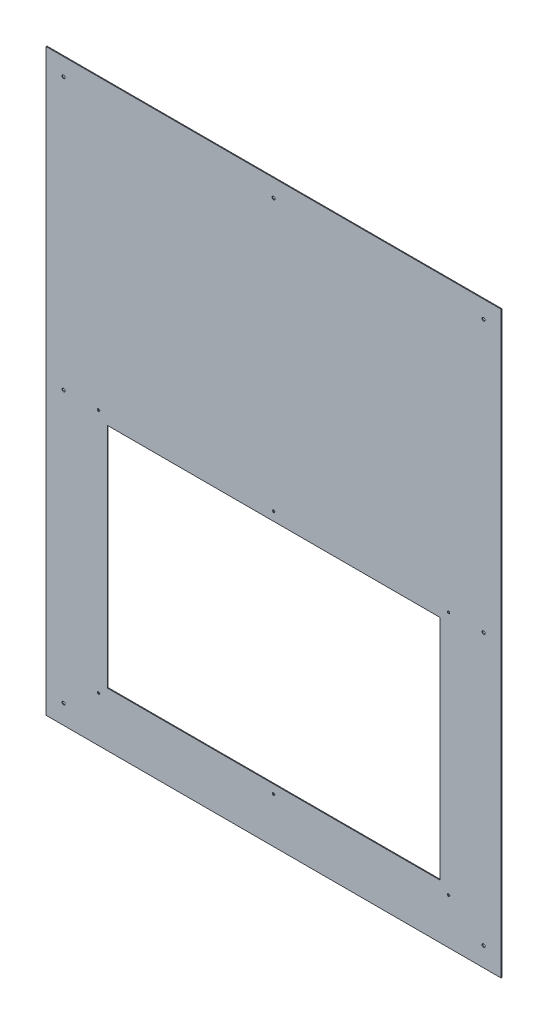
SolidWorks part; units mm, degrees
material "1023 Carbon Steel Sheet (SS)"
ref_plane "Front Plane" through (0, 0, 0) normal (0, 0, 1) x (1, 0, 0)
ref_plane "Top Plane" through (0, 0, 0) normal (0, 1, 0) x (1, 0, 0)
ref_plane "Right Plane" through (0, 0, 0) normal (1, 0, 0) x (0, 0, -1)
sketch "Sketch1" plane through (0, 0, 0) normal (0, 0, 1) x (1, 0, 0)
  line L1 (0, 0) -> (660.4, 0)
  line L2 (0, 0) -> (0, 840.74)
  line L3 (0, 840.74) -> (660.4, 840.74)
  line L4 (660.4, 0) -> (660.4, 840.74)
  dimension "D1" = 840.74
  dimension "D2" = 660.4
extrude "Boss-Extrude1" add sketch "Sketch1" along normal blind 1.2192
sketch "Sketch2" plane through (0, 0, 1.2192) normal (0, 0, 1) x (1, 0, 0)
  line L0 (660.4, 0) -> (660.4, 840.74) construction
  line L1 (25.4, 815.34) -> (635, 815.34) construction
  line L2 (25.4, 815.34) -> (25.4, 27.94) construction
  line L3 (25.4, 27.94) -> (635, 27.94) construction
  line L4 (635, 815.34) -> (635, 27.94) construction
  line L5 (660.4, 840.74) -> (0, 840.74) construction
  line L6 (0, 840.74) -> (0, 0) construction
  point P12 (25.4, 421.64)
  point P13 (25.4, 815.34)
  point P14 (25.4, 27.94)
  point P15 (330.2, 815.34)
  point P16 (635, 421.64)
  point P17 (635, 815.34)
  point P19 (635, 27.94)
  dimension "D1" = 25.4
  dimension "D2" = 25.4
  dimension "D3" = 25.4
  dimension "D4" = 393.7
hole_wizard "#8 Clearance Hole1" positions "Sketch4" profile "Sketch3" hole size "#8" standard "ANSI Inch" end condition through all
sketch "Sketch4" plane through (0, 0, 1.2192) normal (0, 0, 1) x (1, 0, 0)
  point P0 (25.4, 815.34)
  point P2 (330.2, 815.34)
  point P4 (635, 815.34)
  point P11 (25.4, 421.64)
  point P14 (25.4, 27.94)
  point P17 (635, 27.94)
  point P20 (635, 421.64)
sketch "Sketch3" plane through (25.4, 815.34, 1.2192) normal (1, 0, 0) x (0, -1, 0)
  line L0 (0, 0) -> (0, 1.2192)
  line L1 (0, 1.2192) -> (2.2479, 1.2192)
  line L2 (2.2479, 1.2192) -> (2.2479, 0)
  line L5 (2.2479, 0) -> (0, 0)
  line L11 (0, -6.35) -> (0, 107.95) construction
  dimension "Thru Hole Dia." = 4.4958
  dimension "Thru Hole Depth" = 1.2192
sketch "Sketch5" plane through (0, 0, 1.2192) normal (0, 0, 1) x (1, 0, 0)
  line L0 (0, 840.74) -> (0, 0) construction
  line L1 (88.9, 408.94) -> (571.5, 408.94)
  line L2 (88.9, 408.94) -> (88.9, 78.74)
  line L3 (88.9, 78.74) -> (571.5, 78.74)
  line L4 (571.5, 408.94) -> (571.5, 78.74)
  line L7 (660.4, 840.74) -> (0, 840.74) construction
  dimension "D1" = 482.6
  dimension "D2" = 330.2
  dimension "D3" = 88.9
  dimension "D4" = 431.8
extrude "Cut-Extrude1" cut sketch "Sketch5" against normal blind 2.54
sketch "Sketch6" plane through (0, 0, 1.2192) normal (0, 0, 1) x (1, 0, 0)
  line L0 (571.5, 408.94) -> (88.9, 408.94) construction
  line L1 (76.2, 421.64) -> (584.2, 421.64)
  line L2 (76.2, 421.64) -> (76.2, 66.04)
  line L3 (76.2, 66.04) -> (584.2, 66.04)
  line L4 (584.2, 421.64) -> (584.2, 66.04)
  line L5 (88.9, 78.74) -> (571.5, 78.74) construction
  line L6 (571.5, 78.74) -> (571.5, 408.94) construction
  line L7 (88.9, 408.94) -> (88.9, 78.74) construction
  point P12 (330.2, 421.64)
  point P13 (76.2, 421.64)
  point P14 (330.2, 66.04)
  point P15 (584.2, 421.64)
  point P16 (584.2, 66.04)
  point P18 (76.2, 66.04)
  dimension "D1" = 12.7
  dimension "D2" = 12.7
  dimension "D3" = 12.7
  dimension "D4" = 12.7
hole_wizard "Tap Drill for #8-32 Tap1" positions "Sketch8" profile "Sketch7" hole size "#8-32" standard "ANSI Inch"
sketch "Sketch8" plane through (0, 0, 1.2192) normal (0, 0, 1) x (1, 0, 0)
  point P0 (76.2, 421.64)
  point P3 (330.2, 421.64)
  point P6 (584.2, 421.64)
  point P9 (584.2, 66.04)
  point P12 (330.2, 66.04)
  point P15 (76.2, 66.04)
sketch "Sketch7" plane through (76.2, 421.64, 1.2192) normal (1, 0, 0) x (0, -1, 0)
  line L0 (0, 0) -> (0, 26.4378)
  line L1 (0, 26.4378) -> (1.7272, 25.4)
  line L2 (1.7272, 25.4) -> (1.7272, 0)
  line L5 (1.7272, 0) -> (0, 0)
  line L10 (0, 26.4378) -> (-1.7272, 25.4) construction
  line L11 (0, -6.35) -> (0, 107.95) construction
  dimension "Hole Dia." = 3.4544
  dimension "Hole Depth" = 25.4
  dimension "Drill Angle" = 118
equation "\"h\"=33.1"
equation "\"b\"=26"
equation "\"d\"=1"
